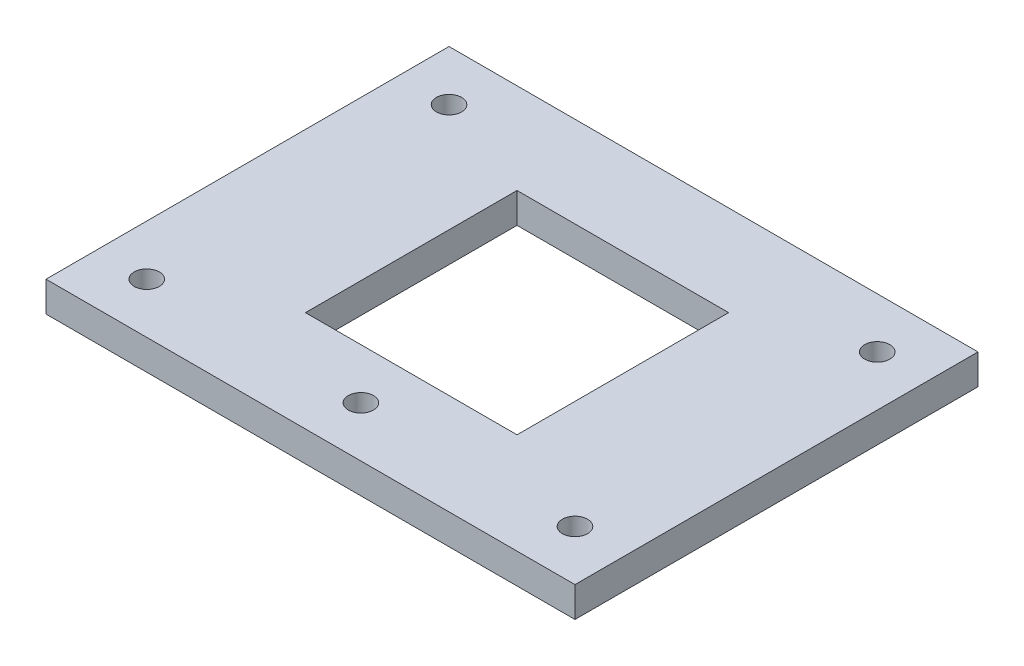
SolidWorks part; units mm, degrees
material "Acrylic (Medium-high impact)"
ref_plane "Front Plane" through (0, 0, 0) normal (0, 0, 1) x (1, 0, 0)
ref_plane "Top Plane" through (0, 0, 0) normal (0, 1, 0) x (1, 0, 0)
ref_plane "Right Plane" through (0, 0, 0) normal (1, 0, 0) x (0, 0, -1)
sketch "Sketch1" plane through (0, 0, 0) normal (0, 1, 0) x (1, 0, 0)
  line L0 (0, 0) -> (-52.5, 0)
  line L1 (-52.5, 0) -> (-52.5, 80)
  line L2 (-52.5, 80) -> (52.5, 80)
  line L3 (52.5, 80) -> (52.5, 0)
  line L4 (52.5, 0) -> (0, 0)
  dimension "D1" = 105
  dimension "D2" = 80
extrude "Boss-Extrude1" add sketch "Sketch1" along normal blind 6
sketch "Sketch2" plane through (0, 6, 0) normal (0, 1, 0) x (1, 0, 0)
  line L0 (-42.5, 70) -> (-42.5, 10) construction
  line L1 (-42.5, 10) -> (42.5, 10) construction
  line L2 (42.5, 10) -> (42.5, 70) construction
  line L3 (42.5, 70) -> (-42.5, 70) construction
  line L4 (-52.5, 80) -> (-52.5, 0) construction
  line L5 (52.5, 0) -> (52.5, 80) construction
  line L6 (-52.5, 0) -> (52.5, 0) construction
  line L7 (52.5, 80) -> (-52.5, 80) construction
  line L8 (0, 0) -> (0, 41) construction
  line L10 (21, 20) -> (-21, 20)
  line L11 (21, 20) -> (21, 62)
  line L12 (21, 62) -> (-21, 62)
  line L13 (-21, 20) -> (-21, 62)
  line L14 (21, 20) -> (-21, 62) construction
  line L15 (21, 62) -> (-21, 20) construction
  circle A0 centre (-42.5, 70) radius 2.5
  circle A1 centre (42.5, 70) radius 2.5
  circle A2 centre (42.5, 10) radius 2.5
  circle A3 centre (0, 10) radius 2.5
  circle A4 centre (-42.5, 10) radius 2.5
  dimension "D1" = 5
  dimension "D6" = 42
  dimension "D2" = 10
  dimension "D3" = 10
  dimension "D4" = 10
  dimension "D5" = 10
  dimension "D7" = 41
extrude "Cut-Extrude1" cut sketch "Sketch2" against normal through all
